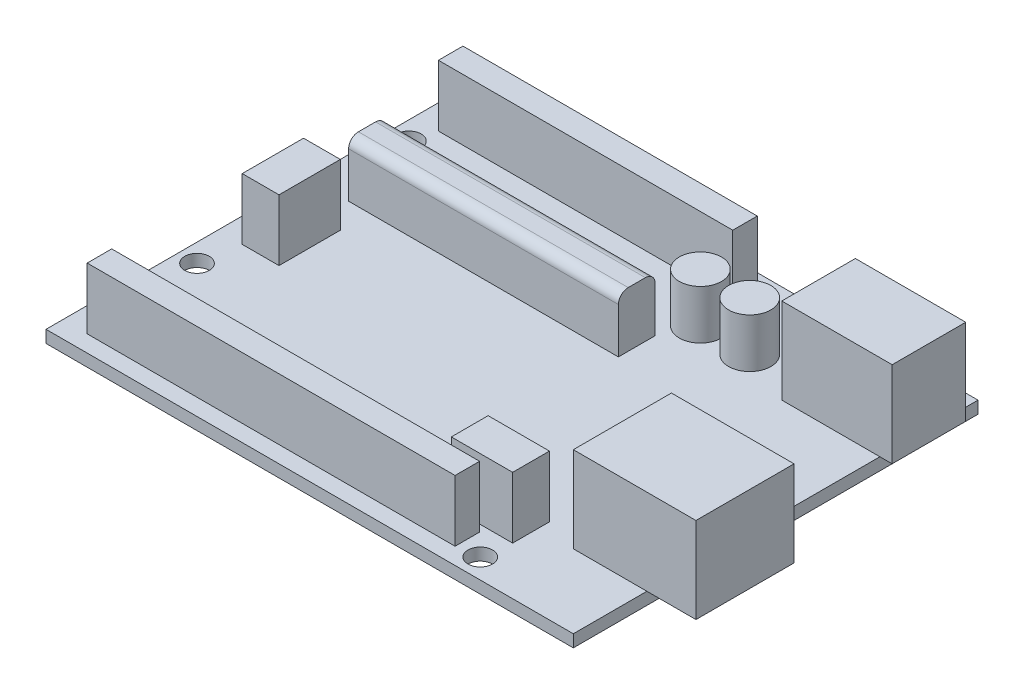
SolidWorks part; units mm, degrees
ref_plane "Front Plane" through (0, 0, 0) normal (0, 0, 1) x (1, 0, 0)
ref_plane "Top Plane" through (0, 0, 0) normal (0, 1, 0) x (1, 0, 0)
ref_plane "Right Plane" through (0, 0, 0) normal (1, 0, 0) x (0, 0, -1)
sketch "Sketch2" plane through (0, 0, 0) normal (0, 1, 0) x (1, 0, 0)
  line L1 (0, 0) -> (68.2625, 0)
  line L2 (0, 0) -> (0, 52.3875)
  line L3 (0, 52.3875) -> (68.2625, 52.3875)
  line L4 (68.2625, 0) -> (68.2625, 52.3875)
  dimension "D1" = 68.2625
  dimension "D2" = 52.3875
extrude "Boss-Extrude1" add sketch "Sketch2" along normal blind 1.5875
sketch "Sketch3" plane through (0, 1.5875, 0) normal (0, 1, 0) x (1, 0, 0)
  line L0 (0, 52.3875) -> (0, 0) construction
  line L1 (3.175, 50.8) -> (41.275, 50.8)
  line L2 (3.175, 50.8) -> (3.175, 47.625)
  line L3 (3.175, 47.625) -> (41.275, 47.625)
  line L4 (41.275, 50.8) -> (41.275, 47.625)
  line L5 (68.2625, 52.3875) -> (0, 52.3875) construction
  line L6 (68.2625, 26.1937) -> (0, 26.1937) construction
  line L7 (3.175, 5.3313) -> (50.8, 5.3313)
  line L8 (3.175, 5.3313) -> (3.175, 2.1563)
  line L9 (3.175, 2.1563) -> (50.8, 2.1563)
  line L10 (50.8, 5.3313) -> (50.8, 2.1563)
  line L11 (3.1796, 30.1596) -> (7.9421, 30.1596)
  line L12 (3.1796, 30.1596) -> (3.1796, 22.2221)
  line L13 (3.1796, 22.2221) -> (7.9421, 22.2221)
  line L14 (7.9421, 30.1596) -> (7.9421, 22.2221)
  line L15 (68.2625, 0) -> (68.2625, 52.3875) construction
  line L16 (3.175, 47.625) -> (3.175, 5.3313) construction
  line L17 (7.9421, 26.1908) -> (3.1796, 26.1908) construction
  line L23 (46.2363, 10.9974) -> (54.1738, 10.9974)
  line L24 (46.2363, 10.9974) -> (46.2363, 6.2349)
  line L25 (46.2363, 6.2349) -> (54.1738, 6.2349)
  line L26 (54.1738, 10.9974) -> (54.1738, 6.2349)
  dimension "D1" = 3.175
  dimension "D2" = 38.1
  dimension "D3" = 3.175
  dimension "D4" = 1.5875
  dimension "D5" = 47.625
  dimension "D6" = 3.175
  dimension "D7" = 4.7625
  dimension "D8" = 7.9375
  dimension "D9" = 4.7625
  dimension "D10" = 7.9375
extrude "Boss-Extrude2" add sketch "Sketch3" along normal blind 7.9375
sketch "Sketch5" plane through (0, 1.5875, 0) normal (0, 1, 0) x (1, 0, 0)
  line L1 (5.2224, 38.7123) -> (40.1474, 38.7123)
  line L2 (5.2224, 38.7123) -> (5.2224, 33.9498)
  line L3 (5.2224, 33.9498) -> (40.1474, 33.9498)
  line L4 (40.1474, 38.7123) -> (40.1474, 33.9498)
  dimension "D1" = 34.925
  dimension "D2" = 4.7625
extrude "Boss-Extrude3" add sketch "Sketch5" along normal blind 7.1437
fillet "Fillet1" radius 1.27 2 edges at (22.6849, 8.7312, -38.7123) (22.6849, 8.7312, -33.9498)
sketch "Sketch6" plane through (0, 1.5875, 0) normal (0, 1, 0) x (1, 0, 0)
  circle A0 centre (41.9702, 42.7427) radius 2.7374
  circle A3 centre (48.3575, 42.7427) radius 2.7374
extrude "Boss-Extrude4" add sketch "Sketch6" along normal blind 6.35
sketch "Sketch7" plane through (0, 1.5875, 0) normal (0, 1, 0) x (1, 0, 0)
  line L0 (0, 0) -> (68.2625, 0) construction
  line L1 (58.7375, 22.225) -> (74.6125, 22.225)
  line L2 (58.7375, 22.225) -> (58.7375, 9.525)
  line L3 (58.7375, 9.525) -> (74.6125, 9.525)
  line L4 (74.6125, 22.225) -> (74.6125, 9.525)
  line L5 (0, 52.3875) -> (0, 0) construction
  dimension "D1" = 15.875
  dimension "D2" = 12.7
  dimension "D3" = 9.525
  dimension "D4" = 58.7375
extrude "Boss-Extrude5" add sketch "Sketch7" along normal blind 11.1125
sketch "Sketch8" plane through (0, 1.5875, 0) normal (0, 1, 0) x (1, 0, 0)
  line L0 (68.2625, 22.225) -> (68.2625, 52.3875) construction
  line L1 (55.5625, 49.2125) -> (69.85, 49.2125)
  line L2 (55.5625, 49.2125) -> (55.5625, 39.6875)
  line L3 (55.5625, 39.6875) -> (69.85, 39.6875)
  line L4 (69.85, 49.2125) -> (69.85, 39.6875)
  line L5 (68.2625, 52.3875) -> (0, 52.3875) construction
  dimension "D1" = 14.2875
  dimension "D2" = 9.525
  dimension "D3" = 1.5875
  dimension "D4" = 3.175
extrude "Boss-Extrude6" add sketch "Sketch8" along normal blind 11.1125
sketch "Sketch9" plane through (0, 0, 0) normal (0, -1, 0) x (1, 0, 0)
  line L0 (2.3813, -44.5997) -> (53.6378, -2.5808) construction
  line L1 (54.4513, -49.8067) -> (2.3812, -17.1677) construction
  line L3 (0, -26.1937) -> (68.2625, -26.1937) construction
  line L4 (0, -52.3875) -> (0, 0) construction
  line L5 (68.2625, -22.225) -> (68.2625, -39.6875) construction
  circle A4 centre (53.6378, -2.5808) radius 1.5875
  circle A5 centre (54.4513, -49.8067) radius 1.5875
  circle A6 centre (2.3813, -44.5997) radius 1.5875
  circle A7 centre (2.3812, -17.1677) radius 1.5875
  point P0 (0, 0)
  dimension "D1" = 66.2784
  dimension "D2" = 52.07
  dimension "D3" = 108.575
  dimension "D4" = 52.07
  dimension "D5" = 47.2259
  dimension "D6" = 2.3813
extrude "Cut-Extrude1" cut sketch "Sketch9" against normal up to surface (1.5875 mm away) up to face at (48.3575, 1.5875, -45.4801)
